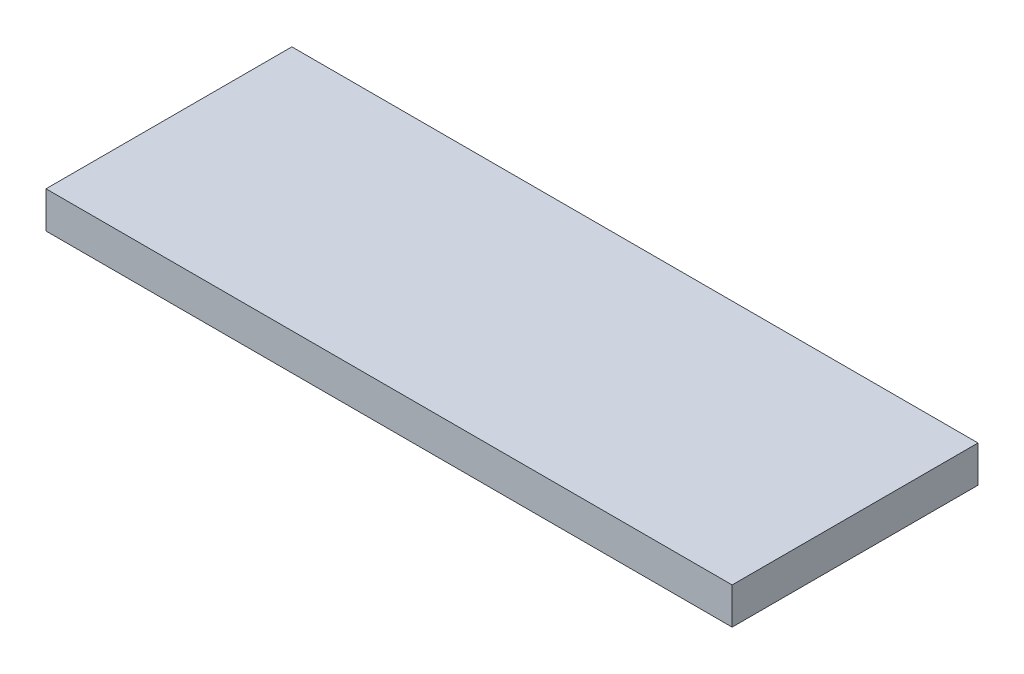
SolidWorks part; units mm, degrees
ref_plane "Front Plane" through (0, 0, 0) normal (0, 0, 1) x (1, 0, 0)
ref_plane "Top Plane" through (0, 0, 0) normal (0, 1, 0) x (1, 0, 0)
ref_plane "Right Plane" through (0, 0, 0) normal (1, 0, 0) x (0, 0, -1)
sketch "Sketch2" plane through (0, 0, 0) normal (0, 1, 0) x (1, 0, 0)
  line L1 (0, 0) -> (30, 0)
  line L2 (0, 0) -> (0, 10.75)
  line L3 (0, 10.75) -> (30, 10.75)
  line L4 (30, 0) -> (30, 10.75)
  dimension "D1" = 30
  dimension "D2" = 10.75
extrude "Boss-Extrude1" add sketch "Sketch2" along normal blind 1.6
equation "\"leftedgewidth\"= 8.5mm"
equation "\"rightedgewidth\"= 10.75mm"
equation "\"innerclipwidth\"= 11.5mm"
equation "\"innerframewidth\"= 99.18mm"
equation "\"framelength\"= 118.4mm"
equation "\"frameextralength\"= 39mm"
equation "\"clipwidth\"= 3mm"
equation "\"cliplength\"= 6mm"
equation "\"clipheight\"= 8mm"
equation "\"basethickness\"= 5mm"
equation "\"framethickness\"= 1.6mm"
equation "\"batterylength\"= 145mm"
equation "\"batterywidth\"= 51mm"
equation "\"D2@Sketch2\"=\"rightedgewidth\""
